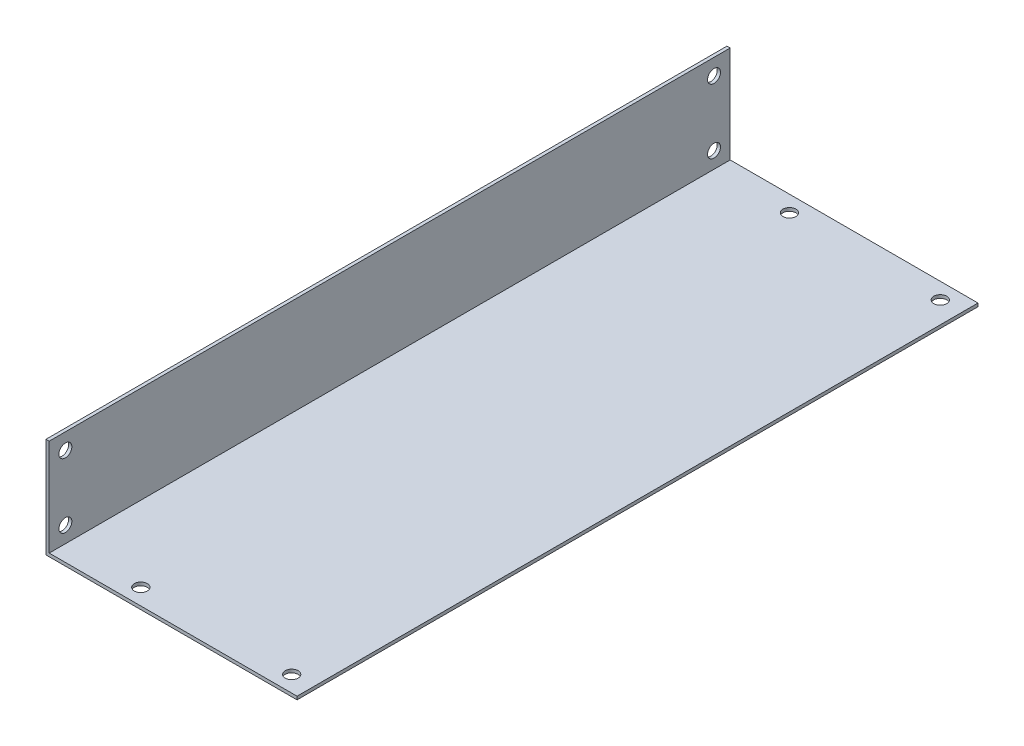
SolidWorks part; units mm, degrees
ref_plane "Front Plane" through (0, 0, 0) normal (0, 0, 1) x (1, 0, 0)
ref_plane "Top Plane" through (0, 0, 0) normal (0, 1, 0) x (1, 0, 0)
ref_plane "Right Plane" through (0, 0, 0) normal (1, 0, 0) x (0, 0, -1)
sketch "Sketch1" plane through (0, 0, 0) normal (0, 0, 1) x (1, 0, 0)
  line L0 (0, 0) -> (0, -46.5)
  line L1 (0, -46.5) -> (116.5, -46.5)
  line L2 (116.5, -46.5) -> (116.5, -45)
  line L3 (116.5, -45) -> (1.5, -45)
  line L4 (1.5, -45) -> (1.5, 0)
  line L5 (1.5, 0) -> (0, 0)
  dimension "D1" = 1.5
  dimension "D2" = 1.5
  dimension "D3" = 116.5
  dimension "D4" = 46.5
extrude "Boss-Extrude1" add sketch "Sketch1" along normal blind 316
sketch "Sketch2" plane through (0, 0, 0) normal (-1, 0, 0) x (0, 0, 1)
  line L0 (0, -23.25) -> (4.5, -23.25) construction
  line L1 (0, 0) -> (0, -46.5) construction
  line L2 (316, 0) -> (316, -46.5) construction
  line L3 (158, 0) -> (158, -46.5) construction
  line L4 (316, 0) -> (0, 0) construction
  line L5 (316, -46.5) -> (0, -46.5) construction
  line L6 (10.5, -23.25) -> (316, -23.25) construction
  circle A2 centre (7.5, -7.5) radius 3
  circle A3 centre (7.5, -37.5) radius 3
  circle A4 centre (308.5, -37.5) radius 3
  circle A5 centre (308.5, -7.5) radius 3
  dimension "D2" = 7.5
  dimension "D5" = 6
  dimension "D6" = 6
  dimension "D1" = 7.5
  dimension "D3" = 9
  dimension "D4" = 7.5
extrude "Cut-Extrude1" cut sketch "Sketch2" against normal up to next
sketch "Sketch3" plane through (0, -46.5, 0) normal (0, -1, 0) x (1, 0, 0)
  line L0 (0, 158) -> (116.5, 158) construction
  line L1 (0, 316) -> (0, 0) construction
  line L2 (116.5, 316) -> (116.5, 0) construction
  line L3 (0, 308.5) -> (116.5, 308.5) construction
  line L4 (0, 7.5) -> (116.5, 7.5) construction
  line L5 (0, 316) -> (116.5, 316) construction
  circle A0 centre (106.5, 308.5) radius 3
  circle A1 centre (36.5, 308.5) radius 3
  circle A2 centre (106.5, 7.5) radius 3
  circle A3 centre (36.5, 7.5) radius 3
  dimension "D2" = 6
  dimension "D3" = 80
  dimension "D1" = 7.5
  dimension "D4" = 10
extrude "Cut-Extrude2" cut sketch "Sketch3" against normal up to next
